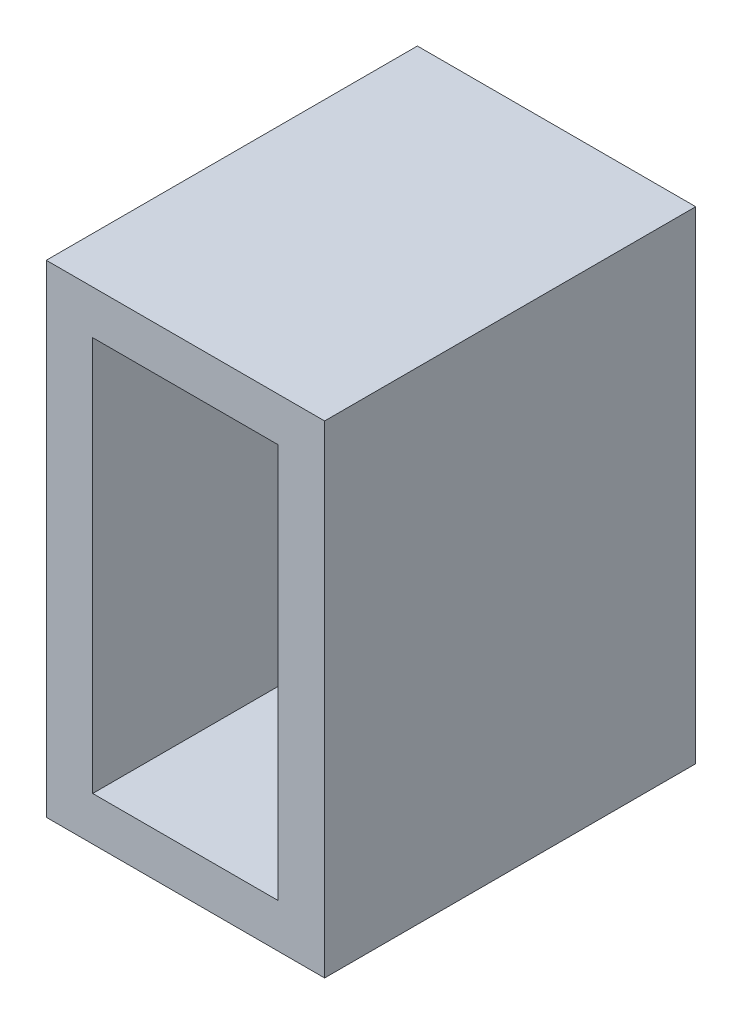
SolidWorks part; units mm, degrees
ref_plane "Front Plane" through (0, 0, 0) normal (0, 0, 1) x (1, 0, 0)
ref_plane "Top Plane" through (0, 0, 0) normal (0, 1, 0) x (1, 0, 0)
ref_plane "Right Plane" through (0, 0, 0) normal (1, 0, 0) x (0, 0, -1)
sketch "Sketch1" plane through (0, 0, 0) normal (0, 0, 1) x (1, 0, 0)
  line L0 (-8.5917, 0.6616) -> (-14.9417, 0.6616) construction
  line L1 (-14.9417, 33.6816) -> (23.1583, 33.6816)
  line L2 (-14.9417, 33.6816) -> (-14.9417, -32.3584)
  line L3 (-14.9417, -32.3584) -> (23.1583, -32.3584)
  line L4 (23.1583, 33.6816) -> (23.1583, -32.3584)
  line L5 (-8.5917, 27.6808) -> (16.8083, 27.6808)
  line L6 (-8.5917, 27.6808) -> (-8.5917, -26.3577)
  line L7 (-8.5917, -26.3577) -> (16.8083, -26.3577)
  line L8 (16.8083, 27.6808) -> (16.8083, -26.3577)
  line L9 (16.8083, 18.3178) -> (23.1583, 18.3178) construction
  line L10 (7.6819, 27.6808) -> (7.6819, 33.6816) construction
  line L11 (7.6819, -26.3577) -> (7.6819, -32.3584) construction
  dimension "D1" = 38.1
  dimension "D2" = 66.04
  dimension "D3" = 6.35
  dimension "D4" = 54.0385
extrude "Boss-Extrude1" add sketch "Sketch1" along normal blind 50.8
ref_plane "Plane1" through (0, 0, 5.588) normal (0, 0, -1) x (-1, 0, 0)
ref_point "Point1"
ref_point "Point2"
sketch "Sketch4" plane through (0, 0, 5.588) normal (0, 0, -1) x (-1, 0, 0)
  line L0 (-4.1083, 20.6006) -> (-4.1083, 27.6808) construction
  line L1 (8.5917, 27.6808) -> (-16.8083, 27.6808) construction
  line L2 (8.5917, 27.6808) -> (8.5917, -26.3577) construction
  line L3 (8.5917, -26.3577) -> (-16.8083, -26.3577) construction
  line L4 (-16.8083, 27.6808) -> (-16.8083, -26.3577) construction
  line L5 (-16.8083, 27.6808) -> (8.5917, 27.6808)
  line L6 (-16.8083, 27.6808) -> (-16.8083, 20.6006)
  line L7 (-16.8083, 20.6006) -> (8.5917, 20.6006)
  line L8 (8.5917, 27.6808) -> (8.5917, 20.6006)
  line L9 (-16.8083, -26.3577) -> (8.5917, -26.3577)
  line L10 (-16.8083, -26.3577) -> (-16.8083, -19.2774)
  line L11 (-16.8083, -19.2774) -> (8.5917, -19.2774)
  line L12 (8.5917, -26.3577) -> (8.5917, -19.2774)
  line L13 (-4.1083, -19.2774) -> (-4.1083, -26.3577) construction
  line L14 (-13.8873, 20.6006) -> (-13.8873, -19.2774)
  line L15 (5.6707, -19.2774) -> (5.6707, 20.6006)
  line L16 (-13.8873, 0.6616) -> (-16.8083, 0.6616) construction
  line L17 (-13.8873, 20.6006) -> (-16.8083, 20.6006)
  line L18 (-13.8873, 20.6006) -> (-13.8873, -19.2774)
  line L19 (-13.8873, -19.2774) -> (-16.8083, -19.2774)
  line L20 (-16.8083, 20.6006) -> (-16.8083, -19.2774)
  line L21 (5.6707, -19.2774) -> (8.5917, -19.2774)
  line L22 (5.6707, -19.2774) -> (5.6707, 20.6006)
  line L23 (5.6707, 20.6006) -> (8.5917, 20.6006)
  line L24 (8.5917, -19.2774) -> (8.5917, 20.6006)
  line L25 (5.6707, 0.6616) -> (8.5917, 0.6616) construction
  dimension "D1" = 39.878
  dimension "D2" = 19.558
extrude "Boss-Extrude2" add sketch "Sketch4" against normal blind 2.54 contours L8 L5 L6 L7 | L7 L20 L11 L14 | L9 L12 L11 L10 | L11 L24 L7 L15
sketch "Sketch5" plane through (0, 0, 5.588) normal (0, 0, -1) x (-1, 0, 0)
  line L0 (-13.8873, 0.6616) -> (-16.8083, 0.6616) construction
  line L1 (-13.8873, 20.6006) -> (-13.8873, -19.2774) construction
  line L2 (-16.8083, 27.6808) -> (-16.8083, -26.3577) construction
  line L3 (5.6707, 0.6616) -> (8.5917, 0.6616) construction
  line L4 (5.6707, -19.2774) -> (5.6707, 20.6006) construction
  line L5 (8.5917, 27.6808) -> (8.5917, -26.3577) construction
  line L7 (-13.8873, -26.3577) -> (-16.8083, -26.3577)
  line L8 (-13.8873, -26.3577) -> (-13.8873, 27.6808)
  line L9 (-13.8873, 27.6808) -> (-16.8083, 27.6808)
  line L10 (-16.8083, -26.3577) -> (-16.8083, 27.6808)
  line L11 (-13.8873, -26.3577) -> (-16.8083, 27.6808) construction
  line L12 (-13.8873, 27.6808) -> (-16.8083, -26.3577) construction
  line L13 (5.6707, -26.3577) -> (8.5917, -26.3577)
  line L14 (5.6707, -26.3577) -> (5.6707, 27.6808)
  line L15 (5.6707, 27.6808) -> (8.5917, 27.6808)
  line L16 (8.5917, -26.3577) -> (8.5917, 27.6808)
  line L17 (5.6707, -26.3577) -> (8.5917, 27.6808) construction
  line L18 (5.6707, 27.6808) -> (8.5917, -26.3577) construction
  point P12 (-15.3478, 0.6616)
  point P18 (7.1312, 0.6616)
extrude "Boss-Extrude3" add sketch "Sketch5" along normal up to surface (5.588 mm away) up to face at (4.1083, 0.6616, 0)
sketch "Sketch6" plane through (0, 0, 5.588) normal (0, 0, -1) x (-1, 0, 0)
  line L0 (-13.8873, 24.1407) -> (5.6707, 24.1407) construction
  line L1 (-13.8873, 27.6808) -> (-13.8873, 20.6006) construction
  line L2 (5.6707, 27.6808) -> (5.6707, 20.6006) construction
  line L3 (-4.1083, 20.6006) -> (-4.1083, 27.6808) construction
  line L4 (-13.8873, 20.6006) -> (5.6707, 20.6006) construction
  line L5 (-13.8873, 27.6808) -> (5.6707, 27.6808) construction
  line L6 (-4.1083, -19.2774) -> (-4.1083, -26.3577) construction
  line L7 (-13.8873, -19.2774) -> (5.6707, -19.2774) construction
  line L8 (-13.8873, -26.3577) -> (5.6707, -26.3577) construction
  line L9 (-13.8873, 20.6006) -> (5.6707, 20.6006) construction
  line L10 (-5.3783, 20.6006) -> (-2.8383, 20.6006)
  line L11 (-5.3783, 20.6006) -> (-5.3783, 27.6808)
  line L12 (-5.3783, 27.6808) -> (-2.8383, 27.6808)
  line L13 (-2.8383, 20.6006) -> (-2.8383, 27.6808)
  line L14 (-5.3783, 20.6006) -> (-2.8383, 27.6808) construction
  line L15 (-5.3783, 27.6808) -> (-2.8383, 20.6006) construction
  line L16 (-5.3783, -26.3577) -> (-2.8383, -26.3577)
  line L17 (-5.3783, -26.3577) -> (-5.3783, -19.2774)
  line L18 (-5.3783, -19.2774) -> (-2.8383, -19.2774)
  line L19 (-2.8383, -26.3577) -> (-2.8383, -19.2774)
  line L20 (-5.3783, -26.3577) -> (-2.8383, -19.2774) construction
  line L21 (-5.3783, -19.2774) -> (-2.8383, -26.3577) construction
  point P18 (-4.1083, 24.1407)
  point P23 (-4.1083, -22.8175)
  dimension "D1" = 2.54
  dimension "D2" = 2.54
extrude "Cut-Extrude1" cut sketch "Sketch6" against normal blind 2.54
